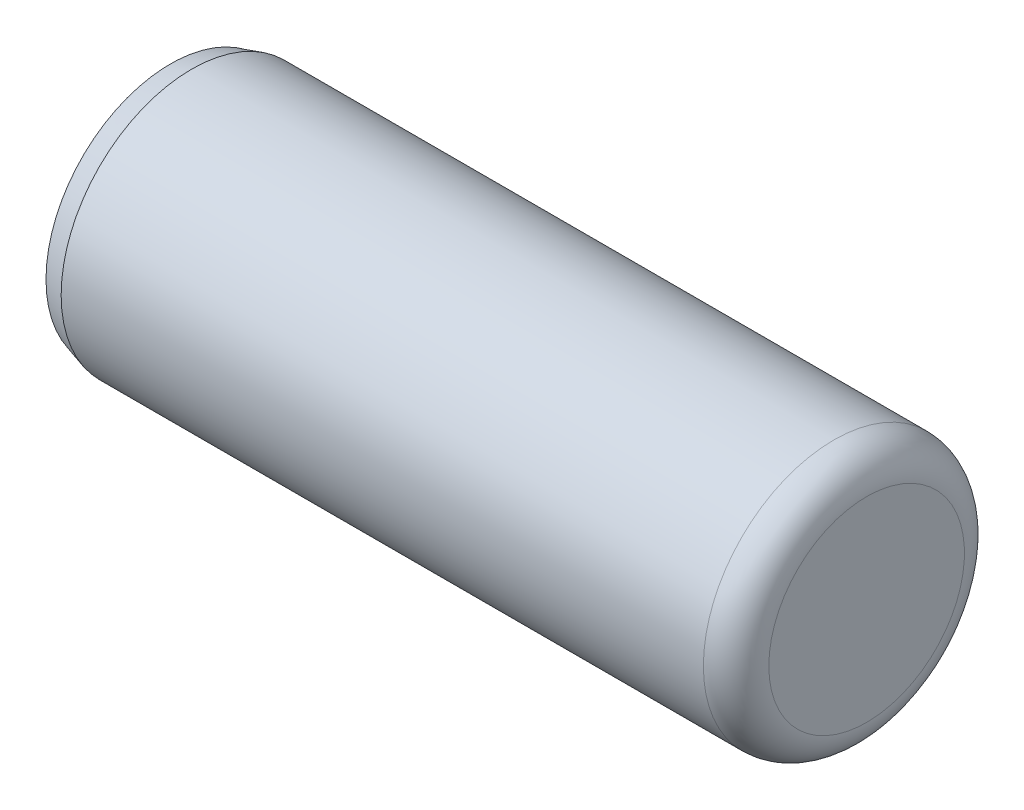
SolidWorks part; units mm, degrees
material "Alloy Steel"
ref_plane "Front" through (0, 0, 0) normal (0, 0, 1) x (1, 0, 0)
ref_plane "Top" through (0, 0, 0) normal (0, 1, 0) x (1, 0, 0)
ref_plane "Right" through (0, 0, 0) normal (1, 0, 0) x (0, 0, -1)
sketch "Sketch1" plane through (0, 0, 0) normal (1, 0, 0) x (0, 0, -1)
  circle A0 centre (0, 0) radius 4.7625 construction
  point P3 (0, 4.7625)
  dimension "Diameter" = 9.525
sketch "Sketch2" plane through (0, 0, 0) normal (0, 0, 1) x (1, 0, 0)
  line L0 (-12.7, 0) -> (12.7, 0) construction
  line L1 (12.7, 3.5687) -> (12.7, -0.6481) construction
  line L2 (-12.7, 4.5403) -> (-12.7, -4.5403) construction
  line L3 (-12.7, 4.5403) -> (-12.7, 4.7625) construction
  line L4 (-12.7, -4.5403) -> (-12.7, -4.7625) construction
  line L5 (-12.7, 4.5403) -> (-11.9249, 4.7625) construction
  line L6 (-11.9249, 4.7625) -> (11.5062, 4.7625) construction
  arc A0 (11.5062, 4.7625) -> (12.7, 3.5687) centre (11.5062, 3.5687) cw construction
  point P6 (-3.175, 0)
  point P8 (3.175, 0)
  point P23 (9.525, 4.7625)
  dimension "Crown Radius" = 1.1938
  dimension "Length" = 25.4
  dimension "D1" = 9.525
  dimension "D2" = 9.525
  dimension "Point Diameter" = 9.0805
  dimension "D3" = 16
  dimension "Crown Height" = 3.175
sketch "Sketch3" plane through (0, 0, 0) normal (0, 0, 1) x (1, 0, 0)
  line L0 (12.7, 3.5687) -> (12.7, -0.6481) construction
  line L1 (-11.9249, 4.7625) -> (11.5062, 4.7625) construction
  line L2 (-12.7, 4.5403) -> (-11.9249, 4.7625) construction
  line L3 (-12.7, 4.5403) -> (-12.7, -4.5403) construction
  line L4 (-12.7, 0) -> (12.7, 0) construction
  line L5 (12.7, 3.5687) -> (12.7, 0)
  line L6 (-11.9249, 4.7625) -> (11.5062, 4.7625)
  line L7 (-12.7, 4.5403) -> (-11.9249, 4.7625)
  line L8 (-12.7, 4.5403) -> (-12.7, 0)
  line L9 (-12.7, 0) -> (12.7, 0)
  arc A0 (12.7, 3.5687) -> (11.5062, 4.7625) centre (11.5062, 3.5687) ccw construction
  arc A1 (12.7, 3.5687) -> (11.5062, 4.7625) centre (11.5062, 3.5687) ccw
revolve "Revolve1" add sketch "Sketch3" angle 360 about L0
equation "\"D1@Sketch2\" = \"Diameter@Sketch1\""
equation "\"D2@Sketch2\" = \"Diameter@Sketch1\""
